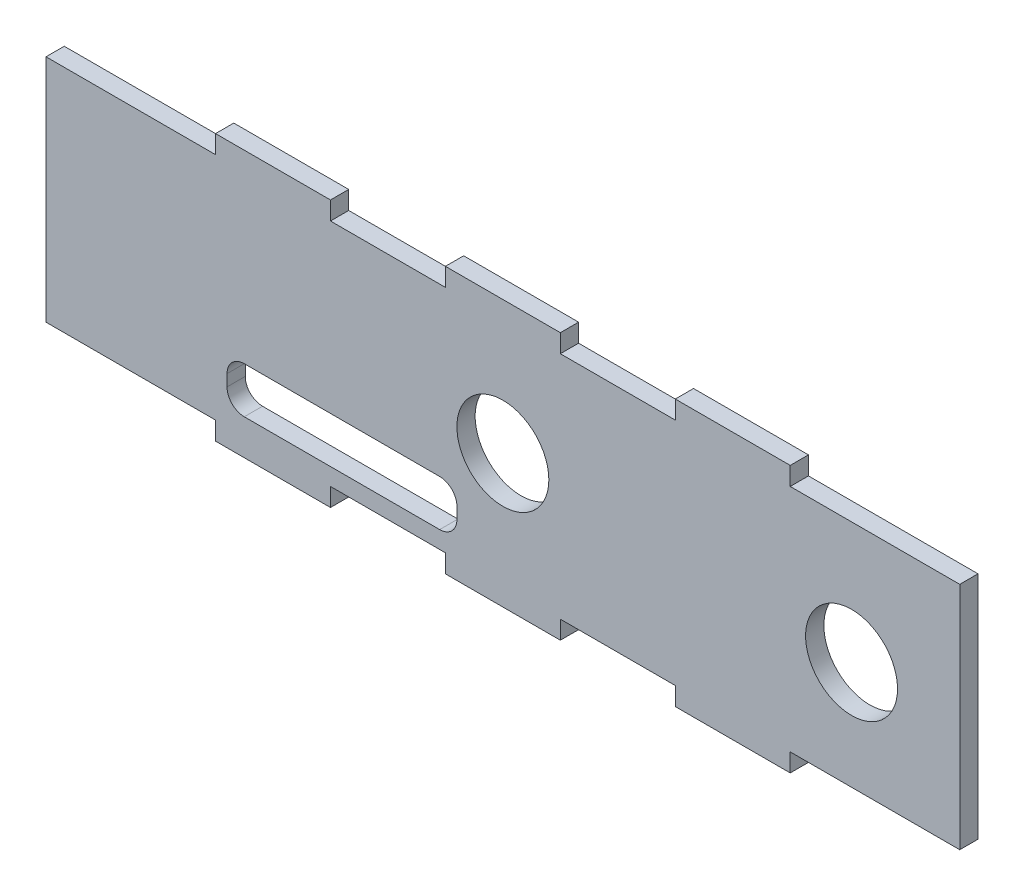
SolidWorks part; units mm, degrees
ref_plane "Plan de face" through (0, 0, 0) normal (0, 0, 1) x (1, 0, 0)
ref_plane "Plan de dessus" through (0, 0, 0) normal (0, 1, 0) x (1, 0, 0)
ref_plane "Plan de droite" through (0, 0, 0) normal (1, 0, 0) x (0, 0, -1)
sketch "Esquisse1" plane through (0, 0, 0) normal (0, 0, 1) x (1, 0, 0)
  line L1 (-82.675, 23.175) -> (82.675, 23.175)
  line L2 (-82.675, 23.175) -> (-82.675, -23.175)
  line L3 (-82.675, -23.175) -> (82.675, -23.175)
  line L4 (82.675, 23.175) -> (82.675, -23.175)
  point P4 (0, -23.175)
  point P6 (82.675, 0)
  dimension "D1" = 165.35
  dimension "D2" = 46.35
extrude "Boss.-Extru.1" add sketch "Esquisse1" along normal blind 3.175
sketch "Esquisse4" plane through (0, 0, 3.175) normal (0, 0, 1) x (1, 0, 0)
  line L0 (-82.675, -23.175) -> (82.675, -23.175) construction
  line L1 (-50, -23.175) -> (-30, -23.175)
  line L2 (-50, -23.175) -> (-50, -20)
  line L3 (-50, -20) -> (-30, -20)
  line L4 (-30, -23.175) -> (-30, -20)
  line L6 (-10, -23.175) -> (10, -23.175)
  line L7 (-10, -23.175) -> (-10, -20)
  line L8 (-10, -20) -> (10, -20)
  line L9 (10, -23.175) -> (10, -20)
  line L10 (30, -23.175) -> (50, -23.175)
  line L11 (30, -23.175) -> (30, -20)
  line L12 (30, -20) -> (50, -20)
  line L13 (50, -23.175) -> (50, -20)
  point P14 (0, -20)
  dimension "D1" = 3.175
  dimension "D2" = 20
  dimension "D3" = 20
  dimension "D4" = 20
sketch "Esquisse5" plane through (0, 0, 3.175) normal (0, 0, 1) x (1, 0, 0)
  line L1 (-30, -23.175) -> (-10, -23.175)
  line L2 (-30, -23.175) -> (-30, -20)
  line L3 (-30, -20) -> (-10, -20)
  line L4 (-10, -23.175) -> (-10, -20)
  line L5 (10, -23.175) -> (30, -23.175)
  line L6 (10, -23.175) -> (10, -20)
  line L7 (10, -20) -> (30, -20)
  line L8 (30, -23.175) -> (30, -20)
  line L9 (50, -23.175) -> (76.325, -23.175)
  line L10 (50, -23.175) -> (50, -20)
  line L11 (50, -20) -> (76.325, -20)
  line L12 (76.325, -23.175) -> (76.325, -20)
  line L14 (-50, -23.175) -> (-76.325, -23.175)
  line L15 (-50, -23.175) -> (-50, -20)
  line L16 (-50, -20) -> (-76.325, -20)
  line L17 (-76.325, -23.175) -> (-76.325, -20)
  line L18 (-50, -20) -> (-30, -20) construction
  line L19 (30, -20) -> (50, -20) construction
  line L21 (82.675, -23.175) -> (82.675, 23.175) construction
  line L23 (-82.675, 23.175) -> (-82.675, -23.175) construction
  dimension "D1" = 6.35
  dimension "D2" = 6.35
extrude "Enlèv. mat.-Extru.2" cut sketch "Esquisse5" against normal through all
mirror "Symétrie2" about plane through (0, 0, 0) normal (0, 1, 0) of "Enlèv. mat.-Extru.2"
sketch "Esquisse7" plane through (0, 0, 3.175) normal (0, 0, 1) x (1, 0, 0)
  line L10 (-82.675, -23.175) -> (-76.325, -23.175) construction
  line L46 (-82.675, 23.175) -> (-79.5, 23.175)
  line L47 (-82.675, 23.175) -> (-82.675, -23.175)
  line L49 (-82.675, -23.175) -> (-79.5, -23.175)
  line L50 (-79.5, 23.175) -> (-79.5, -23.175)
  line L51 (76.325, -23.175) -> (82.675, -23.175) construction
  line L52 (82.675, 23.175) -> (79.5, 23.175)
  line L53 (82.675, 23.175) -> (82.675, -23.175)
  line L54 (82.675, -23.175) -> (79.5, -23.175)
  line L55 (79.5, 23.175) -> (79.5, -23.175)
extrude "Enlèv. mat.-Extru.4" cut sketch "Esquisse7" against normal through all
sketch "Esquisse8" plane through (0, 0, 3.175) normal (0, 0, 1) x (1, 0, 0)
  line L1 (-79.5, 23.175) -> (-76.325, 23.175)
  line L2 (-79.5, 23.175) -> (-79.5, 20)
  line L3 (-79.5, 20) -> (-76.325, 20)
  line L4 (-76.325, 23.175) -> (-76.325, 20)
  line L5 (-79.5, -23.175) -> (-76.325, -23.175)
  line L6 (-79.5, -23.175) -> (-79.5, -20)
  line L7 (-79.5, -20) -> (-76.325, -20)
  line L8 (-76.325, -23.175) -> (-76.325, -20)
  line L9 (79.5, -23.175) -> (76.325, -23.175)
  line L10 (79.5, -23.175) -> (79.5, -20)
  line L11 (79.5, -20) -> (76.325, -20)
  line L12 (76.325, -23.175) -> (76.325, -20)
  line L13 (76.325, 20) -> (79.5, 20)
  line L14 (76.325, 20) -> (76.325, 23.175)
  line L15 (76.325, 23.175) -> (79.5, 23.175)
  line L16 (79.5, 20) -> (79.5, 23.175)
extrude "Enlèv. mat.-Extru.5" cut sketch "Esquisse8" against normal through all
sketch "Esquisse6" plane through (0, 0, 3.175) normal (0, 0, 1) x (1, 0, 0)
  line L1 (30, -23.175) -> (50, -23.175) construction
  line L4 (79.5, 20) -> (79.5, -20) construction
  circle A0 centre (0, 0) radius 8
  circle A1 centre (60.675, -1.175) radius 8
  dimension "D1" = 16
  dimension "D2" = 16
  dimension "D3" = 18.825
  dimension "D4" = 22
extrude "Enlèv. mat.-Extru.3" cut sketch "Esquisse6" against normal through all
sketch "Esquisse9" plane through (0, 0, 3.175) normal (0, 0, 1) x (1, 0, 0)
  line L0 (-50, -20) -> (-79.5, -20) construction
  line L1 (-48, -9) -> (-8, -9)
  line L2 (-48, -9) -> (-48, -17)
  line L3 (-48, -17) -> (-8, -17)
  line L4 (-8, -9) -> (-8, -17)
  dimension "D1" = 40
  dimension "D2" = 8
  dimension "D3" = 3
  dimension "D4" = 8
extrude "Enlèv. mat.-Extru.6" cut sketch "Esquisse9" against normal through all
fillet "Congé1" radius 3 4 edges at (-8, -17, 1.5875) (-8, -9, 1.5875) (-48, -17, 1.5875) (-48, -9, 1.5875)
